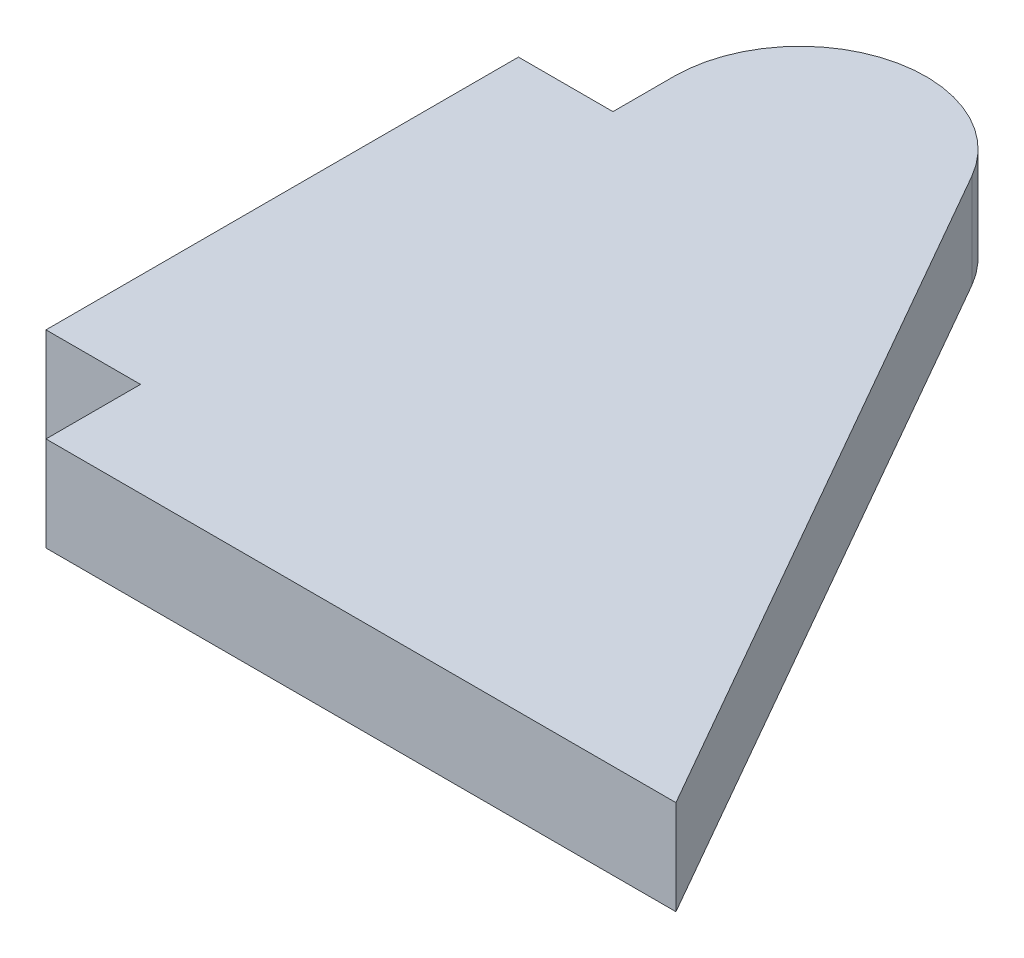
SolidWorks part; units mm, degrees
ref_plane "Plano frontal" through (0, 0, 0) normal (0, 0, 1) x (1, 0, 0)
ref_plane "Plano superior" through (0, 0, 0) normal (0, 1, 0) x (1, 0, 0)
ref_plane "Plano direito" through (0, 0, 0) normal (1, 0, 0) x (0, 0, -1)
sketch "Sketch1" plane through (0, 0, 0) normal (0, 1, 0) x (1, 0, 0)
  line L0 (-10, 17.5) -> (10, -17.5)
  line L1 (-10, 17.5) -> (10, 17.5) construction
  line L2 (-10, 17.5) -> (-10, -17.5)
  line L3 (-10, -17.5) -> (10, -17.5)
  line L4 (10, 17.5) -> (10, -17.5) construction
  point P4 (0, 17.5)
  point P6 (-10, 0)
  dimension "D1" = 35
  dimension "D2" = 20
extrude "Boss-Extrude1" add sketch "Sketch1" along normal mid plane 3
sketch "Sketch2" plane through (0, 0, 0) normal (0, 1, 0) x (1, 0, 0)
  line L0 (-10, 17.5) -> (-10, -17.5) construction
  line L1 (-10, 0.5) -> (-13, 0.5)
  line L2 (-10, 0.5) -> (-10, -14.5)
  line L3 (-10, -14.5) -> (-13, -14.5)
  line L4 (-13, 0.5) -> (-13, -14.5)
  line L5 (-10, -17.5) -> (10, -17.5) construction
  dimension "D1" = 3
  dimension "D2" = 15
  dimension "D3" = 3
extrude "Boss-Extrude2" add sketch "Sketch2" along normal mid plane 3
fillet "Fillet1" radius 4 1 edges at (-10, 0, -17.5)
